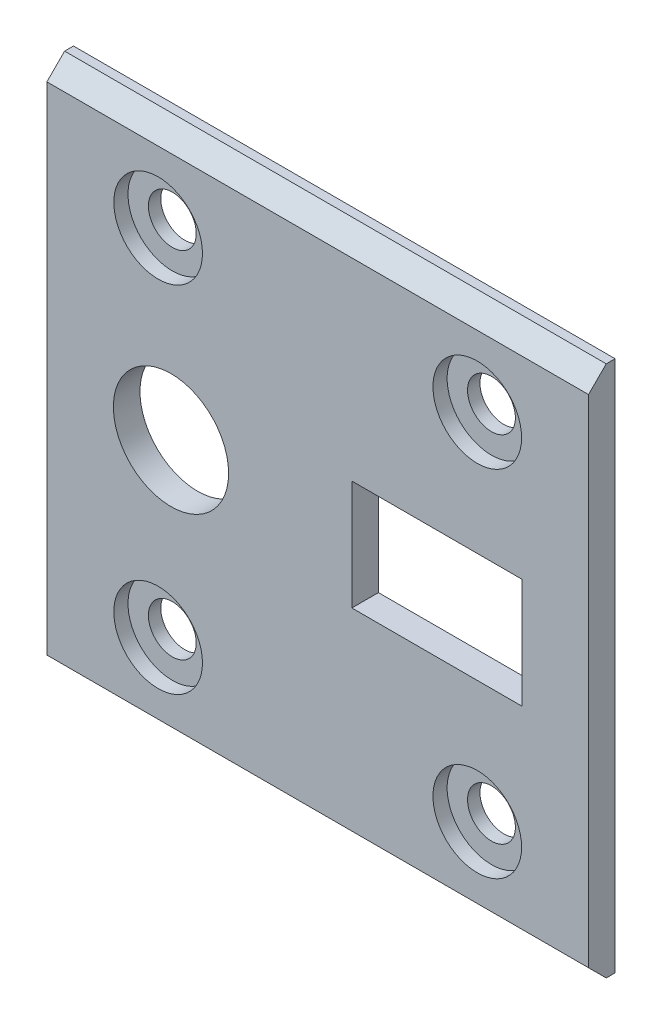
SolidWorks part; units mm, degrees
ref_plane "Piano frontale" through (0, 0, 0) normal (0, 0, 1) x (1, 0, 0)
ref_plane "Piano superiore" through (0, 0, 0) normal (0, 1, 0) x (1, 0, 0)
ref_plane "Piano destro" through (0, 0, 0) normal (1, 0, 0) x (0, 0, -1)
sketch "Schizzo1" plane through (0, 0, 0) normal (0, 0, 1) x (1, 0, 0)
  line L0 (-30.55, 0) -> (30.55, 0) construction
  line L1 (-30.55, 10) -> (30.55, 10)
  line L2 (-30.55, 10) -> (-30.55, -10)
  line L3 (-30.55, -10) -> (30.55, -10)
  line L4 (30.55, 10) -> (30.55, -10)
  line L5 (-30.55, 10) -> (30.55, -10) construction
  line L6 (-30.55, -10) -> (30.55, 10) construction
  line L8 (3.85, 6.2) -> (23.05, 6.2)
  line L9 (3.85, 6.2) -> (3.85, -6.2)
  line L10 (3.85, -6.2) -> (23.05, -6.2)
  line L11 (23.05, 6.2) -> (23.05, -6.2)
  line L12 (3.85, 6.2) -> (23.05, -6.2) construction
  line L13 (3.85, -6.2) -> (23.05, 6.2) construction
  circle A0 centre (-16.55, 0) radius 6.5
  point P0 (0, 0)
  point P10 (13.45, 0)
  dimension "D3" = 13
  dimension "D1" = 20
  dimension "D2" = 7.5
  dimension "D4" = 14
  dimension "D5" = 19.2
  dimension "D6" = 12.4
  dimension "D7" = 30
extrude "Estrusione-Estrusione1" add sketch "Schizzo1" along normal blind 3
sketch "Schizzo5" plane through (0, 0, 3) normal (0, 0, 1) x (1, 0, 0)
  line L1 (30.55, 30) -> (-30.55, 30)
  line L2 (30.55, 30) -> (30.55, 10)
  line L3 (30.55, 10) -> (-30.55, 10)
  line L4 (-30.55, 30) -> (-30.55, 10)
  line L5 (30.55, 30) -> (-30.55, 10) construction
  line L6 (30.55, 10) -> (-30.55, 30) construction
  point P0 (0, 20)
  dimension "D1" = 20
extrude "Estrusione-Estrusione2" add sketch "Schizzo5" against normal blind 3
sketch "Schizzo6" plane through (0, 0, 3) normal (0, 0, 1) x (1, 0, 0)
  line L0 (-30.55, 20) -> (30.55, 20) construction
  line L1 (-30.55, 30) -> (-30.55, -10) construction
  line L2 (30.55, -10) -> (30.55, 30) construction
  line L3 (30.55, 30) -> (-30.55, 30) construction
  line L4 (-30.55, 30) -> (-30.55, -10) construction
  circle A0 centre (-18, 20) radius 2.7
  circle A1 centre (18, 20) radius 2.7
  dimension "D4" = 5.4
  dimension "D1" = 10
  dimension "D2" = 36
  dimension "D3" = 12.55
extrude "Taglio-Estrusione1" cut sketch "Schizzo6" against normal blind 3
sketch "Schizzo7" plane through (0, 0, 3) normal (0, 0, 1) x (1, 0, 0)
  circle A0 centre (-18, 20) radius 5
  circle A1 centre (18, 20) radius 5
  dimension "D1" = 10
extrude "Taglio-Estrusione2" cut sketch "Schizzo7" against normal blind 1.6
mirror "Specchia2" about plane through (0, 0, 0) normal (0, 1, 0) of "Taglio-Estrusione1", "Estrusione-Estrusione2", "Taglio-Estrusione2"
chamfer "Smusso1" distance 2 angle 45 2 edges at (0, -30, 3) (0, 30, 3)
